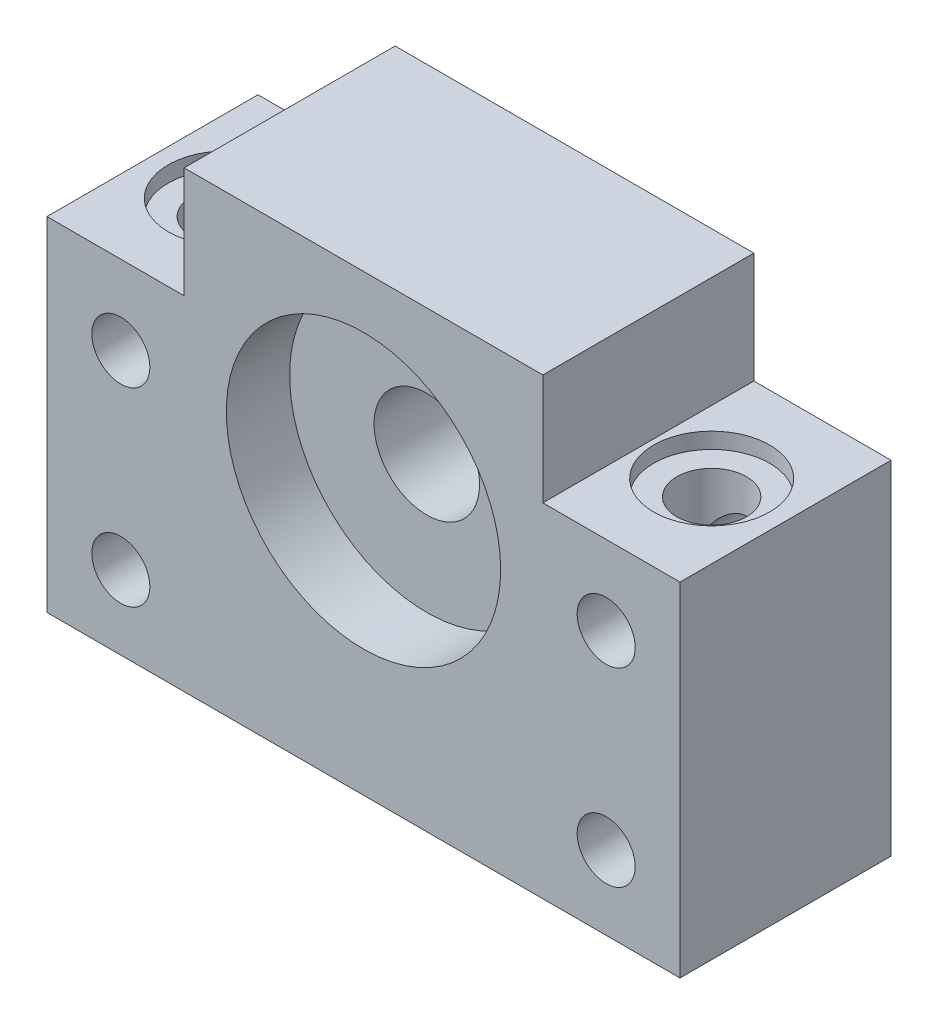
SolidWorks part; units mm, degrees
ref_plane "Alzado" through (0, 0, 0) normal (0, 0, 1) x (1, 0, 0)
ref_plane "Planta" through (0, 0, 0) normal (0, 1, 0) x (1, 0, 0)
ref_plane "Vista lateral" through (0, 0, 0) normal (1, 0, 0) x (0, 0, -1)
sketch "Croquis1" plane through (0, 0, 0) normal (0, 0, 1) x (1, 0, 0)
  line L0 (0, 0) -> (60, 0)
  line L1 (60, 0) -> (60, 32.5)
  line L2 (60, 32.5) -> (47, 32.5)
  line L3 (47, 32.5) -> (47, 43)
  line L4 (47, 43) -> (13, 43)
  line L5 (13, 43) -> (13, 32.5)
  line L6 (13, 32.5) -> (0, 32.5)
  line L7 (0, 32.5) -> (0, 0)
  line L8 (30, 43) -> (30, 0.9008) construction
  line L10 (7, 7) -> (53, 7) construction
  line L11 (7, 7) -> (7, 25) construction
  line L12 (7, 25) -> (53, 25) construction
  line L13 (53, 7) -> (53, 25) construction
  line L14 (7, 7) -> (53, 25) construction
  line L15 (7, 25) -> (53, 7) construction
  circle A0 centre (30, 25) radius 13 construction
  circle A1 centre (7, 25) radius 2.75
  circle A2 centre (53, 25) radius 2.75
  circle A3 centre (53, 7) radius 2.75
  circle A4 centre (7, 7) radius 2.75
  point P13 (30, 16)
  dimension "D6" = 26
  dimension "D7" = 25
  dimension "D10" = 0
  dimension "D11" = 5.5
  dimension "D1" = 43
  dimension "D2" = 32.5
  dimension "D3" = 60
  dimension "D4" = 34
  dimension "D5" = 13
  dimension "D8" = 46
  dimension "D9" = 18
extrude "Saliente-Extruir1" add sketch "Croquis1" along normal blind 20
sketch "Croquis2" plane through (0, 0, 20) normal (0, 0, 1) x (1, 0, 0)
  circle A0 centre (30, 25) radius 5
  dimension "D1" = 10
extrude "Cortar-Extruir1" cut sketch "Croquis2" against normal blind 20
sketch "Croquis3" plane through (0, 0, 20) normal (0, 0, 1) x (1, 0, 0)
  circle A0 centre (30, 25) radius 13
  dimension "D1" = 26
extrude "Cortar-Extruir2" cut sketch "Croquis3" against normal blind 6
sketch "Croquis4" plane through (0, 0, 0) normal (0, 0, -1) x (-1, 0, 0)
  circle A0 centre (-30, 25) radius 13
  dimension "D1" = 26
extrude "Cortar-Extruir3" cut sketch "Croquis4" against normal blind 6
sketch "Croquis5" plane through (0, 32.5, 0) normal (0, 1, 0) x (1, 0, 0)
  line L0 (0, -10) -> (60, -10) construction
  line L1 (0, -20) -> (0, 0) construction
  line L2 (60, -20) -> (60, 0) construction
  line L3 (9.75, 0) -> (4.25, -20) construction
  line L4 (4.25, 0) -> (9.75, -20) construction
  line L5 (55.75, 0) -> (50.25, -20) construction
  line L6 (50.25, 0) -> (55.75, -20) construction
  line L7 (13, -20) -> (0, -20) construction
  circle A0 centre (7, -10) radius 3.3
  circle A1 centre (53, -10) radius 3.3
  dimension "D1" = 6.6
  dimension "D2" = 10
extrude "Cortar-Extruir4" cut sketch "Croquis5" against normal through all
sketch "Croquis6" plane through (0, 32.5, 0) normal (0, 1, 0) x (1, 0, 0)
  circle A0 centre (7, -10) radius 5.5
  circle A1 centre (53, -10) radius 5.5
  dimension "D1" = 11
extrude "Cortar-Extruir5" cut sketch "Croquis6" against normal blind 1.5
